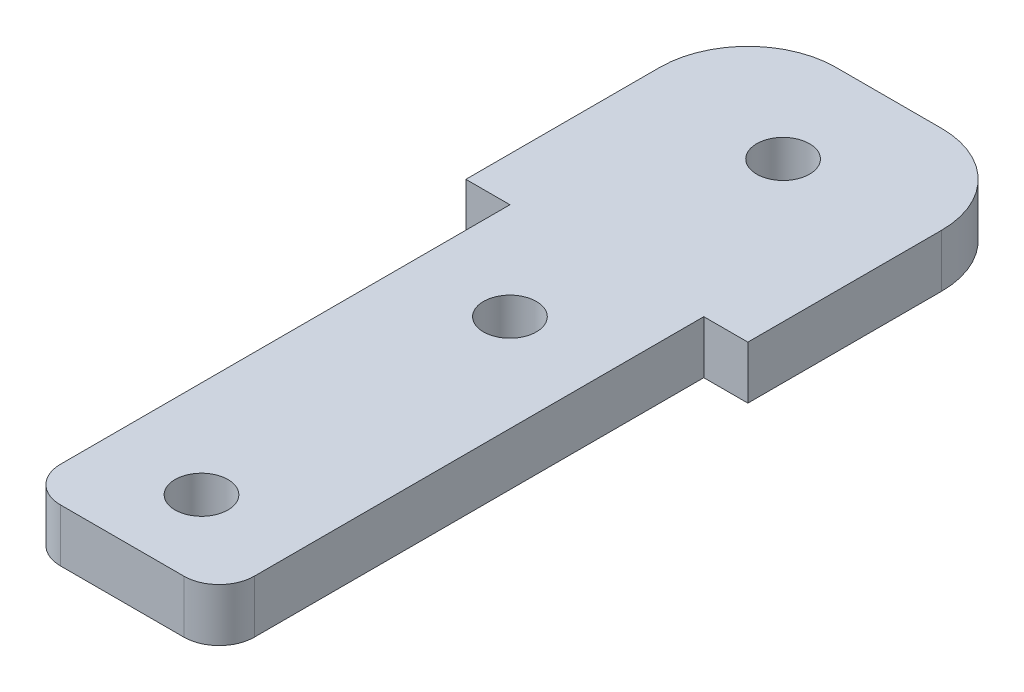
SolidWorks part; units mm, degrees
ref_plane "Front Plane" through (0, 0, 0) normal (0, 0, 1) x (1, 0, 0)
ref_plane "Top Plane" through (0, 0, 0) normal (0, 1, 0) x (1, 0, 0)
ref_plane "Right Plane" through (0, 0, 0) normal (1, 0, 0) x (0, 0, -1)
sketch "Sketch3" plane through (0, 0, 0) normal (0, 1, 0) x (1, 0, 0)
  line L0 (0, 0) -> (0, -23) construction
  line L1 (-6, 5) -> (6, 5)
  line L2 (-8, 3) -> (-8, 0)
  line L3 (-8, 0) -> (8, 0)
  line L4 (8, 3) -> (8, 0)
  line L5 (-5.5, 0) -> (5.5, 0)
  line L6 (-5.5, 0) -> (-5.5, -25.5)
  line L7 (-3.5, -27.5) -> (3.5, -27.5)
  line L8 (5.5, 0) -> (5.5, -25.5)
  circle A0 centre (0, -5.5) radius 1.5
  circle A1 centre (0, -23) radius 1.5
  arc A2 (3.5, -27.5) -> (5.5, -25.5) centre (3.5, -25.5) ccw
  arc A3 (-5.5, -25.5) -> (-3.5, -27.5) centre (-3.5, -25.5) ccw
  arc A4 (6, 5) -> (8, 3) centre (6, 3) cw
  arc A5 (-6, 5) -> (-8, 3) centre (-6, 3) ccw
  point P15 (5.5, -27.5)
  point P18 (-5.5, -27.5)
  point P23 (-8, 5)
  dimension "D8" = 3
  dimension "D9" = 3
  dimension "D10" = 5.5
  dimension "D11" = 17.5
  dimension "D12" = 2
  dimension "D1" = 5
  dimension "D2" = 0
  dimension "D3" = 8
  dimension "D4" = 8
  dimension "D5" = 11
  dimension "D6" = 2.5
  dimension "D7" = 27.5
extrude "Boss-Extrude1" add sketch "Sketch3" along normal blind 3
sketch "Sketch4" plane through (0, 3, 0) normal (0, 1, 0) x (1, 0, 0)
  line L1 (-8, 0) -> (8, 0)
  line L2 (-8, 0) -> (-8, 11)
  line L3 (-3, 16) -> (3, 16)
  line L4 (8, 0) -> (8, 11)
  arc A0 (3, 16) -> (8, 11) centre (3, 11) cw
  arc A1 (-8, 11) -> (-3, 16) centre (-3, 11) cw
  dimension "D3" = 5
  dimension "D1" = 16
  dimension "D2" = 16
extrude "Boss-Extrude2" add sketch "Sketch4" against normal blind 3
sketch "Sketch5" plane through (0, 0, 0) normal (0, -1, 0) x (-1, 0, 0)
  line L0 (-8, 11) -> (-8, 0) construction
  circle A0 centre (0, 10) radius 1.5
  dimension "D1" = 10
  dimension "D3" = 3
  dimension "D2" = 8
extrude "Cut-Extrude1" cut sketch "Sketch5" against normal blind 3
